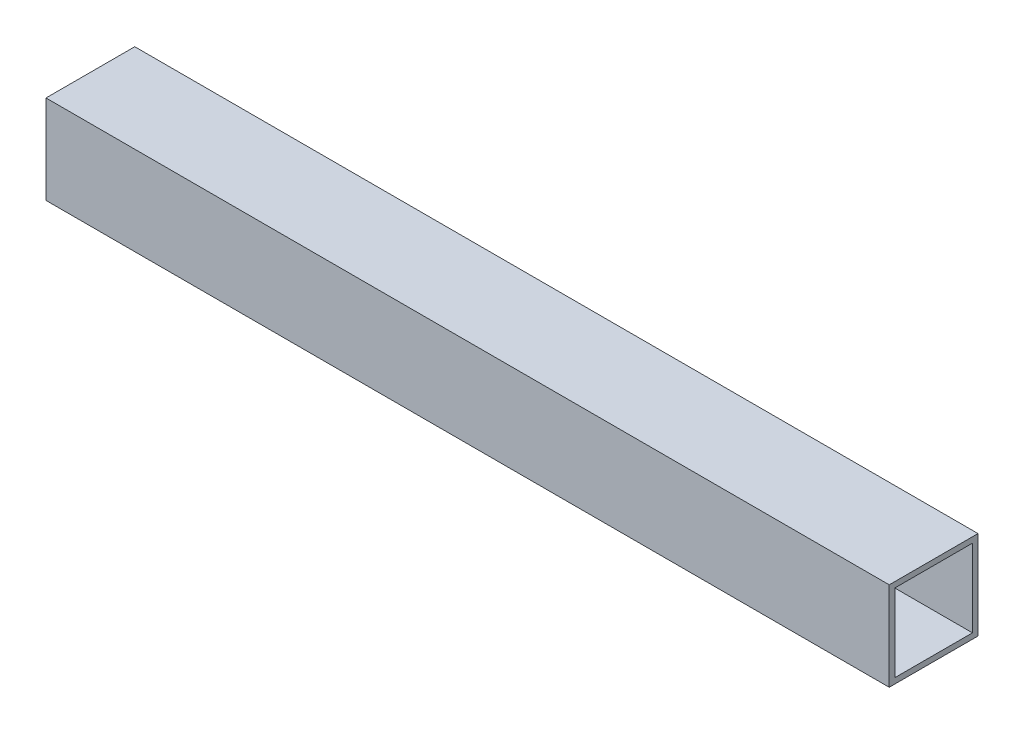
SolidWorks part; units mm, degrees
material "6061-T6 (SS)"
ref_plane "Alzado" through (0, 0, 0) normal (0, 0, 1) x (1, 0, 0)
ref_plane "Planta" through (0, 0, 0) normal (0, 1, 0) x (1, 0, 0)
ref_plane "Vista lateral" through (0, 0, 0) normal (1, 0, 0) x (0, 0, -1)
sketch "Croquis2" plane through (0, 0, 0) normal (1, 0, 0) x (0, 0, -1)
  line L0 (-22.225, 22.225) -> (-22.225, -22.225)
  line L1 (-25.4, 25.4) -> (25.4, 25.4)
  line L2 (-25.4, 25.4) -> (-25.4, -25.4)
  line L3 (-25.4, -25.4) -> (25.4, -25.4)
  line L4 (25.4, 25.4) -> (25.4, -25.4)
  line L5 (-25.4, 25.4) -> (25.4, -25.4) construction
  line L6 (-25.4, -25.4) -> (25.4, 25.4) construction
  line L7 (-22.225, -22.225) -> (22.225, -22.225)
  line L8 (22.225, 22.225) -> (22.225, -22.225)
  line L9 (-22.225, 22.225) -> (22.225, 22.225)
  point P0 (0, 0)
  dimension "D2" = 50.8
  dimension "D3" = 50.8
  dimension "D1" = 3.175
extrude "Extrución Base" add sketch "Croquis2" along normal mid plane 482.6
equation "\"Largo\"= 19pulgadas"
equation "\"B\" = 2pulgadas"
equation "\"H\"= 2pulgadas"
equation "\"Grosor\"= 0.125"
equation "\"D1@Croquis2\"=\"Grosor\""
equation "\"D2@Croquis2\"=\"H\""
equation "\"D3@Croquis2\"=\"B\""
equation "\"D1@Extrución Base\" = \"Largo\""
